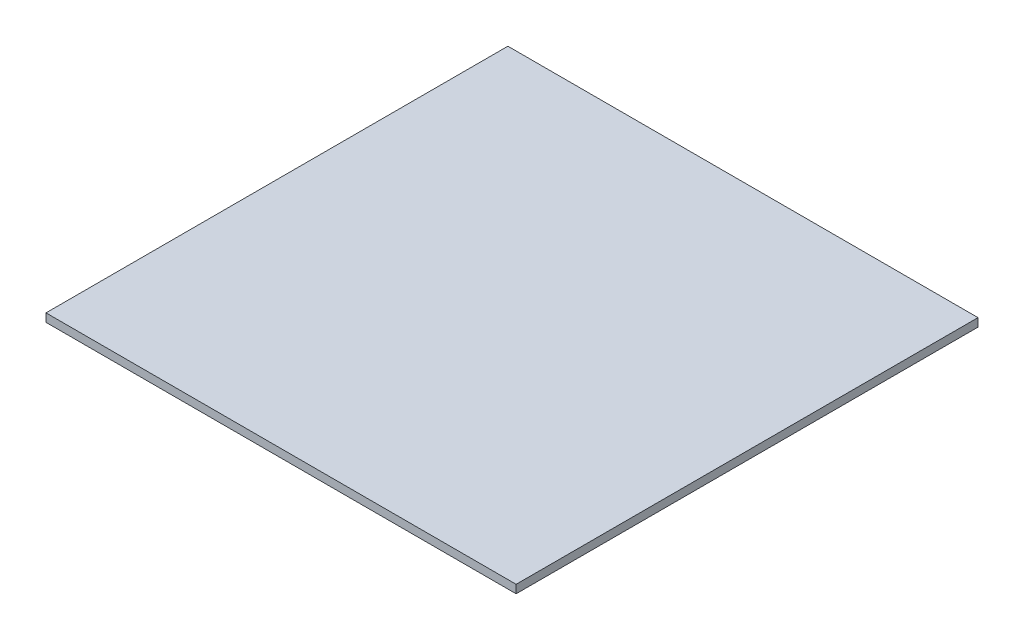
SolidWorks part; units mm, degrees
ref_plane "Front Plane" through (0, 0, 0) normal (0, 0, 1) x (1, 0, 0)
ref_plane "Top Plane" through (0, 0, 0) normal (0, 1, 0) x (1, 0, 0)
ref_plane "Right Plane" through (0, 0, 0) normal (1, 0, 0) x (0, 0, -1)
sketch "Sketch1" plane through (0, 0, 0) normal (0, 1, 0) x (1, 0, 0)
  line L1 (90.4875, -88.9) -> (-90.4875, -88.9)
  line L2 (90.4875, -88.9) -> (90.4875, 88.9)
  line L3 (90.4875, 88.9) -> (-90.4875, 88.9)
  line L4 (-90.4875, -88.9) -> (-90.4875, 88.9)
  line L5 (90.4875, -88.9) -> (-90.4875, 88.9) construction
  line L6 (90.4875, 88.9) -> (-90.4875, -88.9) construction
  point P0 (0, 0)
  dimension "D1" = 180.975
  dimension "D2" = 177.8
extrude "Boss-Extrude1" add sketch "Sketch1" along normal blind 3.175
